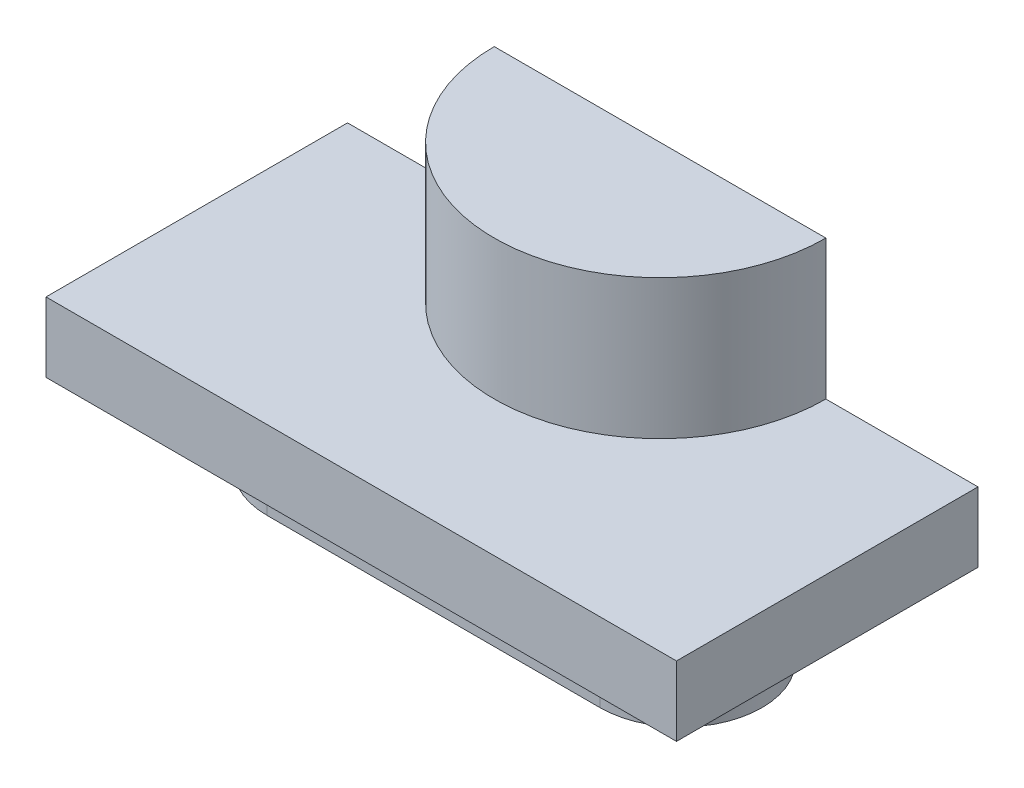
SolidWorks part; units mm, degrees
ref_plane "前视基准面" through (0, 0, 0) normal (0, 0, 1) x (1, 0, 0)
ref_plane "上视基准面" through (0, 0, 0) normal (0, 1, 0) x (1, 0, 0)
ref_plane "右视基准面" through (0, 0, 0) normal (1, 0, 0) x (0, 0, -1)
other "Configuration Table"
sketch "草图1" plane through (0, 0, 0) normal (0, 1, 0) x (1, 0, 0)
  line L1 (0, 0) -> (90.4507, 0)
  line L2 (0, 0) -> (0, 43.2552)
  line L3 (0, 43.2552) -> (90.4507, 43.2552)
  line L4 (90.4507, 0) -> (90.4507, 43.2552)
extrude "凸台-拉伸1" add sketch "草图1" along normal blind 10
sketch "草图2" plane through (0, 10, 0) normal (0, 1, 0) x (1, 0, 0)
  line L4 (0, 43.2552) -> (0, 0)
  line L5 (0, 0) -> (90.4507, 0)
  line L6 (90.4507, 0) -> (90.4507, 43.2552)
  line L7 (90.4507, 43.2552) -> (0, 43.2552)
  line L8 (0, 43.2552) -> (0, 0)
  line L9 (0, 0) -> (90.4507, 0)
  line L10 (90.4507, 0) -> (90.4507, 43.2552)
  line L11 (90.4507, 43.2552) -> (0, 43.2552)
  circle A0 centre (44.8388, 43.2552) radius 23.7914
  dimension "D1" = 0
extrude "凸台-拉伸2" add sketch "草图2" along normal blind 20 contours L11 A0
sketch "草图3" plane through (0, 0, 0) normal (0, -1, 0) x (1, 0, 0)
  line L0 (22.9983, -20.3068) -> (70.8027, -20.3068) construction
  line L1 (22.9983, -8.7101) -> (70.8027, -8.7101)
  line L2 (22.9983, -31.9036) -> (70.8027, -31.9036)
  line L4 (0, 0) -> (0, -43.2552)
  line L5 (0, -43.2552) -> (90.4507, -43.2552)
  line L6 (90.4507, -43.2552) -> (90.4507, 0)
  line L7 (90.4507, 0) -> (0, 0)
  line L8 (0, 0) -> (0, -43.2552)
  line L9 (0, -43.2552) -> (90.4507, -43.2552)
  line L10 (90.4507, -43.2552) -> (90.4507, 0)
  line L11 (90.4507, 0) -> (0, 0)
  arc A0 (22.9983, -8.7101) -> (22.9983, -31.9036) centre (22.9983, -20.3068) ccw
  arc A1 (70.8027, -31.9036) -> (70.8027, -8.7101) centre (70.8027, -20.3068) ccw
  point P6 (46.9005, -20.3068)
  dimension "D1" = 0
extrude "凸台-拉伸3" add sketch "草图3" along normal blind 10
